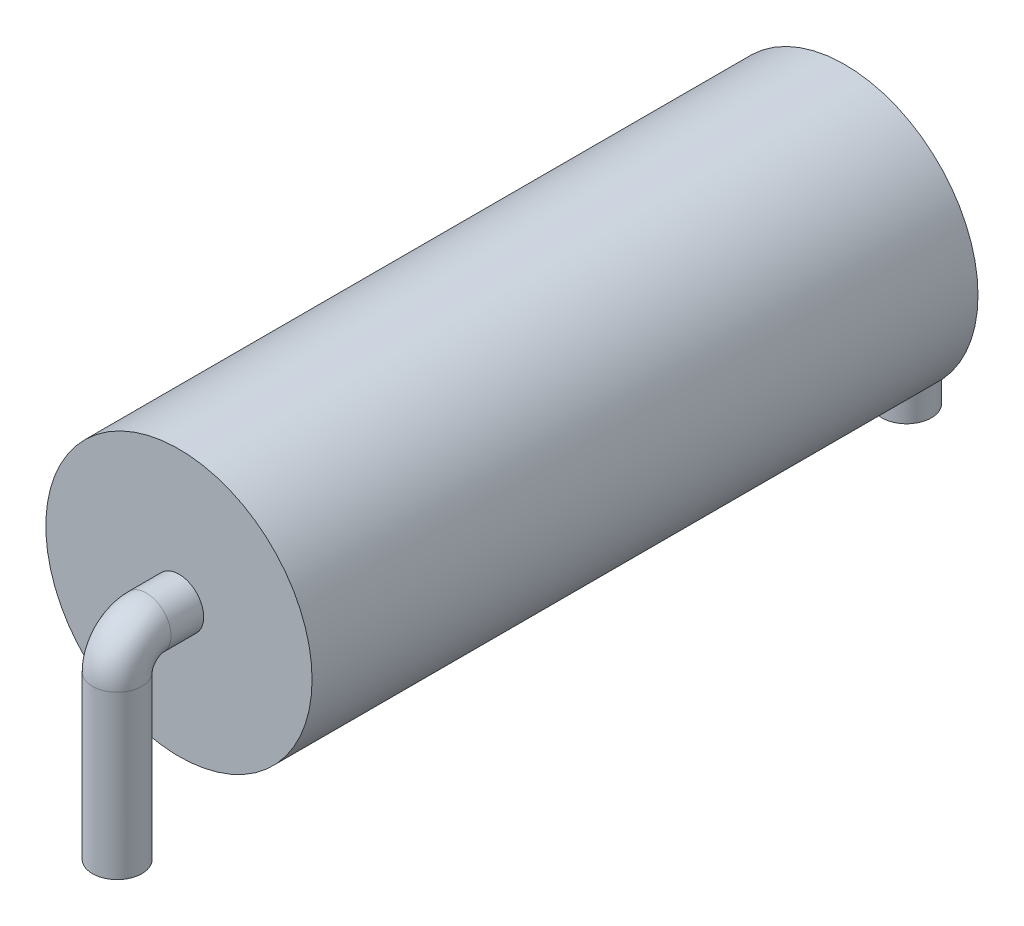
SolidWorks part; units mm, degrees
ref_plane "Front Plane" through (0, 0, 0) normal (0, 0, 1) x (1, 0, 0)
ref_plane "Top Plane" through (0, 0, 0) normal (0, 1, 0) x (1, 0, 0)
ref_plane "Right Plane" through (0, 0, 0) normal (1, 0, 0) x (0, 0, -1)
sketch "Sketch1" plane through (0, 0, 0) normal (0, 0, 1) x (1, 0, 0)
  circle A0 centre (0, 0) radius 2.285
  dimension "D1" = 4.57
extrude "Boss-Extrude1" add sketch "Sketch1" along normal mid plane 11.43 contours A0
sketch "Sketch2" plane through (0, 0, 0) normal (1, 0, 0) x (0, 0, -1)
  line L0 (6.275, 0) -> (-6.275, 0)
  line L1 (-6.775, -0.5) -> (-6.775, -3.285)
  line L2 (0, 0) -> (0, -3.5108) construction
  line L3 (-5.715, -2.285) -> (5.715, -2.285) construction
  line L4 (6.775, -0.5) -> (6.775, -3.285)
  arc A0 (-6.275, 0) -> (-6.775, -0.5) centre (-6.275, -0.5) ccw
  arc A1 (6.275, 0) -> (6.775, -0.5) centre (6.275, -0.5) cw
  dimension "D1" = 13.55
  dimension "D2" = 0.5
  dimension "D3" = 1
sweep "Sweep1" add path "Sketch2" circular profile diameter 0.85 parameters "D3"=0.85
